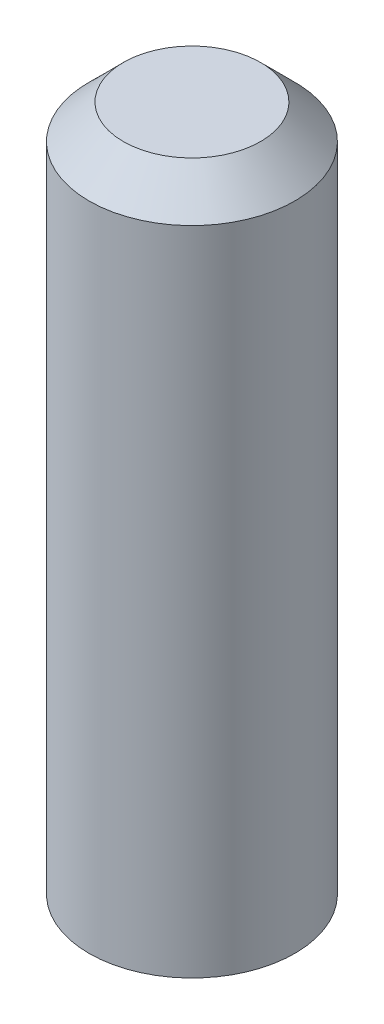
SolidWorks part; units mm, degrees
material "1060 Сплав"
ref_plane "Front" through (0, 0, 0) normal (0, 0, 1) x (1, 0, 0)
ref_plane "Top" through (0, 0, 0) normal (0, 1, 0) x (1, 0, 0)
ref_plane "Right" through (0, 0, 0) normal (1, 0, 0) x (0, 0, -1)
sketch "Эскиз1" plane through (0, 0, 0) normal (0, 1, 0) x (1, 0, 0)
  circle A0 centre (0, 0) radius 1.5
  dimension "D1" = 3
extrude "Бобышка-Вытянуть1" add sketch "Эскиз1" along normal blind 10
chamfer "Фаска1" distance 0.5 angle 45 1 edges at (0, 10, 1.5)
